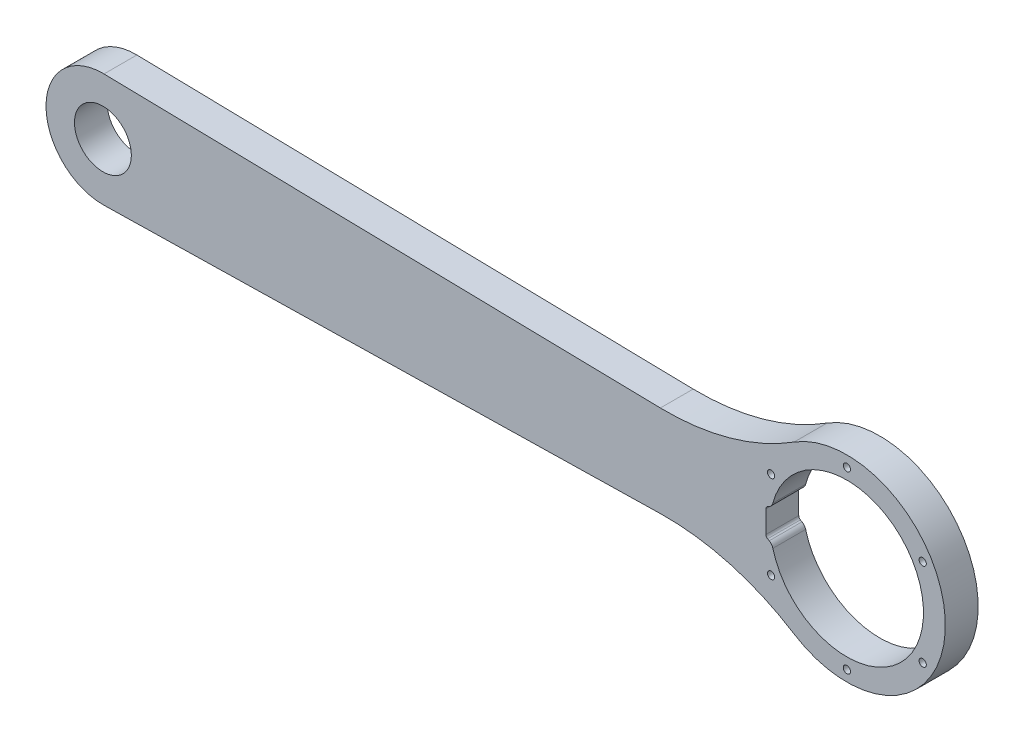
SolidWorks part; units mm, degrees
ref_plane "前视基准面" through (0, 0, 0) normal (0, 0, 1) x (1, 0, 0)
ref_plane "上视基准面" through (0, 0, 0) normal (0, 1, 0) x (1, 0, 0)
ref_plane "右视基准面" through (0, 0, 0) normal (1, 0, 0) x (0, 0, -1)
sketch "草图1" plane through (0, 0, 0) normal (0, 0, 1) x (1, 0, 0)
  line L0 (0, 0) -> (0, 46.9214) construction
  line L1 (0, 0) -> (75.8039, 0) construction
  line L2 (-85.2451, 20.9004) -> (-339.4791, 25.9948)
  line L3 (-85.2451, -20.9004) -> (-339.4791, -25.9948)
  line L4 (-35.5001, 6.7904) -> (-36.238, 6.3734)
  line L5 (-37, 5.0675) -> (-37, -5.0675)
  line L8 (-30.9669, 5.9447) -> (-28.6669, 5.9455) construction
  line L9 (-35.5001, -6.7904) -> (-36.238, -6.3734)
  line L10 (-29.6741, 7.5384) -> (-26.4741, 7.5394) construction
  circle A0 centre (0, 40) radius 1.65
  arc A1 (0, 38.35) -> (0, 41.65) centre (0, 40) ccw construction
  circle A2 centre (34.641, 20) radius 1.65
  circle A3 centre (34.641, -20) radius 1.65
  arc A4 (34.641, 18.35) -> (34.641, 21.65) centre (34.641, 20) ccw construction
  circle A5 centre (0, -40) radius 1.65
  arc A6 (0, -41.65) -> (0, -38.35) centre (0, -40) ccw construction
  circle A7 centre (-34.641, 20) radius 1.65
  arc A8 (-34.641, 21.65) -> (-34.641, 18.35) centre (-34.641, 20) ccw construction
  circle A9 centre (-34.641, -20) radius 1.65
  circle A10 centre (0, 0) radius 35 construction
  arc A12 (-33.8381, 8.9432) -> (-33.8381, -8.9432) centre (0, 0) cw
  arc A13 (-24.1088, 37.9969) -> (-24.1088, -37.9969) centre (0, 0) cw
  circle A14 centre (-340, 0) radius 13
  arc A15 (-85.2451, -20.9004) -> (-24.1088, -37.9969) centre (-83.0414, -130.8783) cw
  arc A16 (-24.1088, 37.9969) -> (-85.2451, 20.9004) centre (-83.0414, 130.8783) cw
  arc A17 (-339.4791, 25.9948) -> (-339.4791, -25.9948) centre (-340, 0) ccw
  arc A18 (-35.5001, -6.7904) -> (-33.8381, -8.9432) centre (-37.2219, -9.8375) cw
  arc A19 (-33.8381, 8.9432) -> (-35.5001, 6.7904) centre (-37.2219, 9.8375) cw
  arc A20 (-36.238, -6.3734) -> (-37, -5.0675) centre (-35.5, -5.0675) cw
  arc A21 (-36.238, 6.3734) -> (-37, 5.0675) centre (-35.5, 5.0675) ccw
  point P48 (-40.3113, -20)
  point P51 (-40.3113, 20)
  point P60 (-37, 0)
  point P63 (-35, 0)
  point P70 (-34.1789, -7.537)
  point P73 (-34.1789, 7.537)
  point P76 (-37, -5.9428)
  point P79 (-37, 5.9428)
  dimension "D1" = 70
  dimension "D2" = 45
  dimension "D4" = 110
  dimension "D5" = 26
  dimension "D7" = 26
  dimension "D9" = 3.5
  dimension "D10" = 1.5
  dimension "D3" = 20
  dimension "D6" = 340
  dimension "D8" = 2
extrude "凸台-拉伸1" add sketch "草图1" along normal blind 15 contours L2 A17 L3 A15 A13 A16
sketch "草图2" plane through (0, 0, 0) normal (0, 0, 1) x (1, 0, 0)
  line L0 (-376.6145, -430.0012) -> (356.6217, 230.2077) construction
